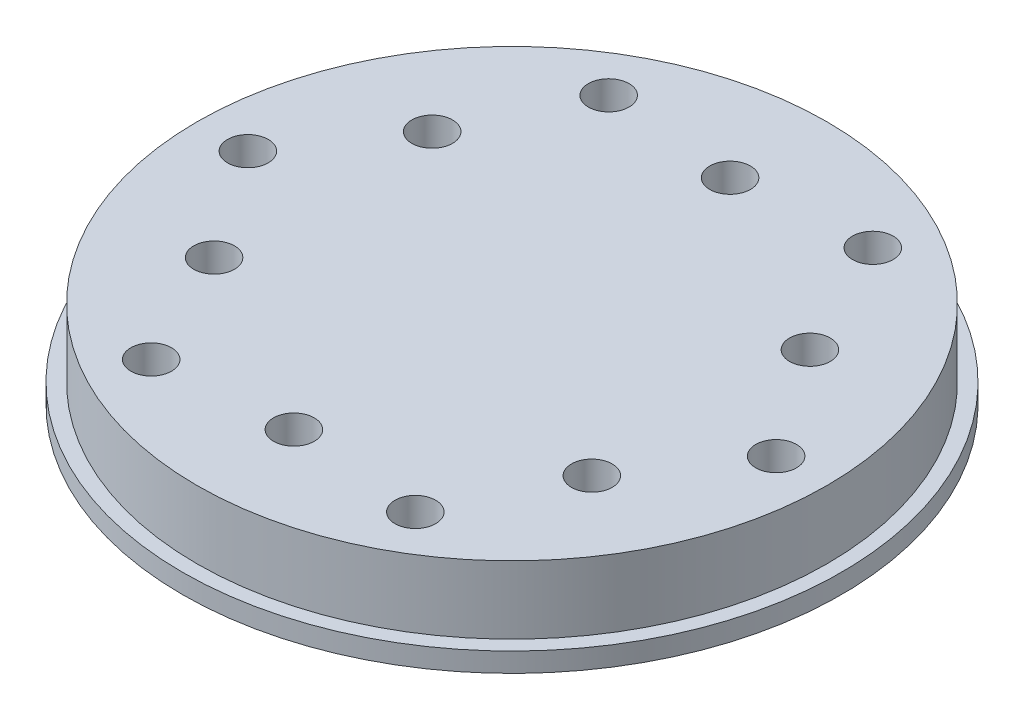
SolidWorks part; units mm, degrees
ref_plane "Front Plane" through (0, 0, 0) normal (0, 0, 1) x (1, 0, 0)
ref_plane "Top Plane" through (0, 0, 0) normal (0, 1, 0) x (1, 0, 0)
ref_plane "Right Plane" through (0, 0, 0) normal (1, 0, 0) x (0, 0, -1)
sketch "Sketch2" plane through (0, 0, 0) normal (0, 1, 0) x (1, 0, 0)
  circle A0 centre (0, 0) radius 27.25 construction
  circle A1 centre (0, 0) radius 32.5
  circle A2 centre (0, 0) radius 6.5
  circle A3 centre (27.25, 0) radius 1.5
  circle A4 centre (13.625, -23.5992) radius 1.5
  circle A5 centre (-13.625, -23.5992) radius 1.5
  circle A6 centre (-27.25, 0) radius 1.5
  circle A7 centre (-13.625, 23.5992) radius 1.5
  circle A8 centre (13.625, 23.5992) radius 1.5
  point P22 (0, 0)
  dimension "D1" = 54.5
  dimension "D4" = 3
  dimension "D3" = 13
  dimension "D2" = 65
  dimension "D5" = 6
extrude "Boss-Extrude1" add sketch "Sketch2" along normal blind 10
hole_wizard "M5x0.8 Tapped Hole1" positions "Sketch6" profile "Sketch7" tap size "M5x0.8" standard "ANSI Metric" end condition through all
sketch "Sketch6" plane through (0, 10, 0) normal (0, 1, 0) x (1, 0, 0)
  point P0 (-13.625, 23.5992)
  point P8 (13.625, 23.5992)
  point P9 (27.25, 0)
  point P10 (13.625, -23.5992)
  point P11 (-13.625, -23.5992)
  point P12 (-27.25, 0)
  dimension "D1" = 6
sketch "Sketch7" plane through (-13.625, 10, -23.5992) normal (1, 0, 0) x (0, 0, 1)
  line L0 (0, 0) -> (0, 10)
  line L1 (0, 10) -> (2.1, 10)
  line L2 (2.1, 10) -> (2.1, 0)
  line L5 (2.1, 0) -> (0, 0)
  line L11 (0, -6.35) -> (0, 107.95) construction
  dimension "Thru Tap Drill Dia." = 4.2
  dimension "Thru Tap Drill Depth" = 10
cosmetic thread "Hole Thread1"
cosmetic thread "Hole Thread2"
cosmetic thread "Hole Thread3"
cosmetic thread "Hole Thread4"
cosmetic thread "Hole Thread5"
cosmetic thread "Hole Thread6"
sketch "Sketch8" plane through (0, 10, 0) normal (0, 1, 0) x (1, 0, 0)
  circle A0 centre (0, 0) radius 6.5 construction
  circle A1 centre (0, 0) radius 6.5
extrude "Boss-Extrude2" add sketch "Sketch8" against normal blind 6.5
sketch "Sketch9" plane through (0, 0, 0) normal (0, -1, 0) x (1, 0, 0)
  circle A0 centre (0, 0) radius 32.5 construction
  circle A1 centre (0, 0) radius 32.5
  circle A2 centre (0, 0) radius 17.5
  dimension "D1" = 35
extrude "Cut-Extrude1" cut sketch "Sketch9" against normal blind 1
sketch "Sketch10" plane through (0, 0, 0) normal (1, 0, 0) x (0, 0, -1)
  line L0 (0, 0) -> (0, 10) construction
  line L1 (-32.5, 1) -> (-34, 1)
  line L2 (-32.5, 1) -> (-32.5, 3)
  line L3 (-32.5, 3) -> (-34, 3)
  line L4 (-34, 1) -> (-34, 3)
  line L5 (2.1, 10) -> (-2.1, 10) construction
  dimension "D1" = 2
  dimension "D2" = 1.5
revolve "Revolve1" add sketch "Sketch10" angle 360 about L0
hole_wizard "M5x0.8 Tapped Hole2" positions "Sketch11" profile "Sketch12" tap size "M5x0.8" standard "ANSI Metric" end condition through all
sketch "Sketch11" plane through (0, 10, 0) normal (0, 1, 0) x (1, 0, 0)
  line L0 (0, 0) -> (0, 32.5) construction
  circle A0 centre (0, 0) radius 32.5 construction
  point P0 (0, 22.5)
  point P19 (19.4856, 11.25)
  point P21 (19.4856, -11.25)
  point P23 (0, -22.5)
  point P25 (-19.4856, -11.25)
  point P27 (-19.4856, 11.25)
  dimension "D1" = 10
  dimension "D2" = 10
  dimension "D3" = 6
sketch "Sketch12" plane through (0, 10, -22.5) normal (1, 0, 0) x (0, 0, 1)
  line L0 (0, 0) -> (0, 10)
  line L1 (0, 10) -> (2.1, 10)
  line L2 (2.1, 10) -> (2.1, 0)
  line L5 (2.1, 0) -> (0, 0)
  line L11 (0, -6.35) -> (0, 107.95) construction
  dimension "Thru Tap Drill Dia." = 4.2
  dimension "Thru Tap Drill Depth" = 10
cosmetic thread "Hole Thread8"
cosmetic thread "Hole Thread10"
cosmetic thread "Hole Thread12"
cosmetic thread "Hole Thread14"
cosmetic thread "Hole Thread16"
cosmetic thread "Hole Thread18"
